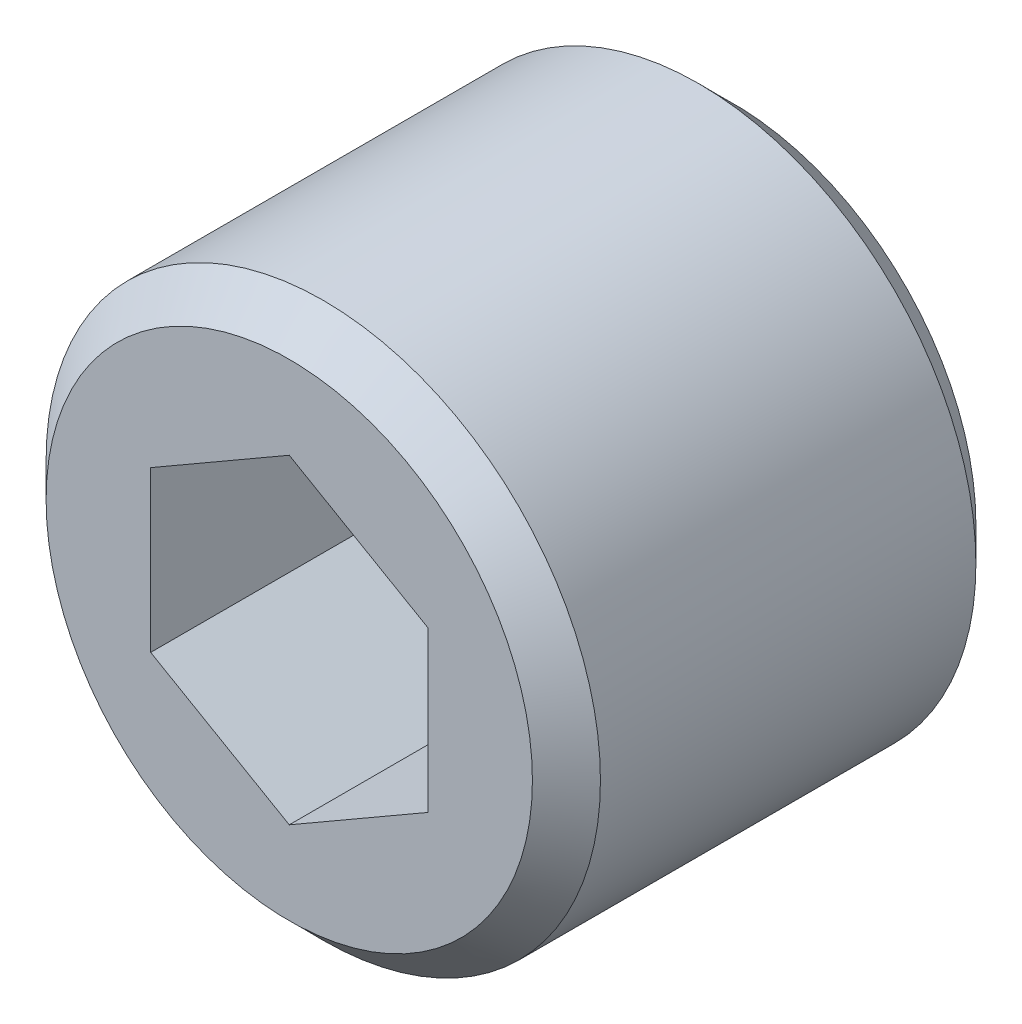
SolidWorks part; units mm, degrees
ref_plane "Płaszczyzna przednia" through (0, 0, 0) normal (0, 0, 1) x (1, 0, 0)
ref_plane "Płaszczyzna górna" through (0, 0, 0) normal (0, 1, 0) x (1, 0, 0)
ref_plane "Płaszczyzna prawa" through (0, 0, 0) normal (1, 0, 0) x (0, 0, -1)
ref_plane "Płaszczyzna1" through (0, 0, 8) normal (0, 0, 1) x (1, 0, 0)
sketch "Szkic1" plane through (0, 0, 0) normal (1, 0, 0) x (0, 0, -1)
  line L0 (-8, 0) -> (-8, 4.3865)
  line L1 (-8, 4.3865) -> (-7.3865, 5)
  line L2 (-7.3865, 5) -> (-0.6135, 5)
  line L3 (-0.6135, 5) -> (0, 4.3865)
  line L4 (0, 4.3865) -> (0, 0)
  line L5 (0, 0) -> (-8, 0)
  line L6 (0, 0) -> (-8, 0) construction
revolve "Obrót1" add sketch "Szkic1" angle 360 about L6
cosmetic thread "Oznaczenie gwintu1" parameters "D1"=8, "D2"=8.773
sketch "Szkic2" plane through (0, 0, 0) normal (1, 0, 0) x (0, 0, -1)
  line L0 (-8, 0) -> (-8, 3.3868)
  line L1 (-8, 3.3868) -> (-4, 3.3868)
  line L2 (-4, 3.3868) -> (-2.0447, 0)
  line L3 (-2.0447, 0) -> (-8, 0)
  line L4 (-2.0447, 0) -> (-8, 0) construction
revolve "Wycięcie-obrót1" cut sketch "Szkic2" angle 360 about L4
sketch "Szkic3" plane through (0, 0, 8) normal (0, 0, 1) x (1, 0, 0)
  line L0 (-2.5, 1.4434) -> (-2.5, -1.4434)
  line L1 (-2.5, -1.4434) -> (0, -2.8868)
  line L2 (0, -2.8868) -> (2.5, -1.4434)
  line L3 (2.5, -1.4434) -> (2.5, 1.4434)
  line L4 (2.5, 1.4434) -> (0, 2.8868)
  line L5 (0, 2.8868) -> (-2.5, 1.4434)
  circle A0 centre (0, 0) radius 3.5868
extrude "Dodanie-wyciągnięcie1" add sketch "Szkic3" against normal blind 6
